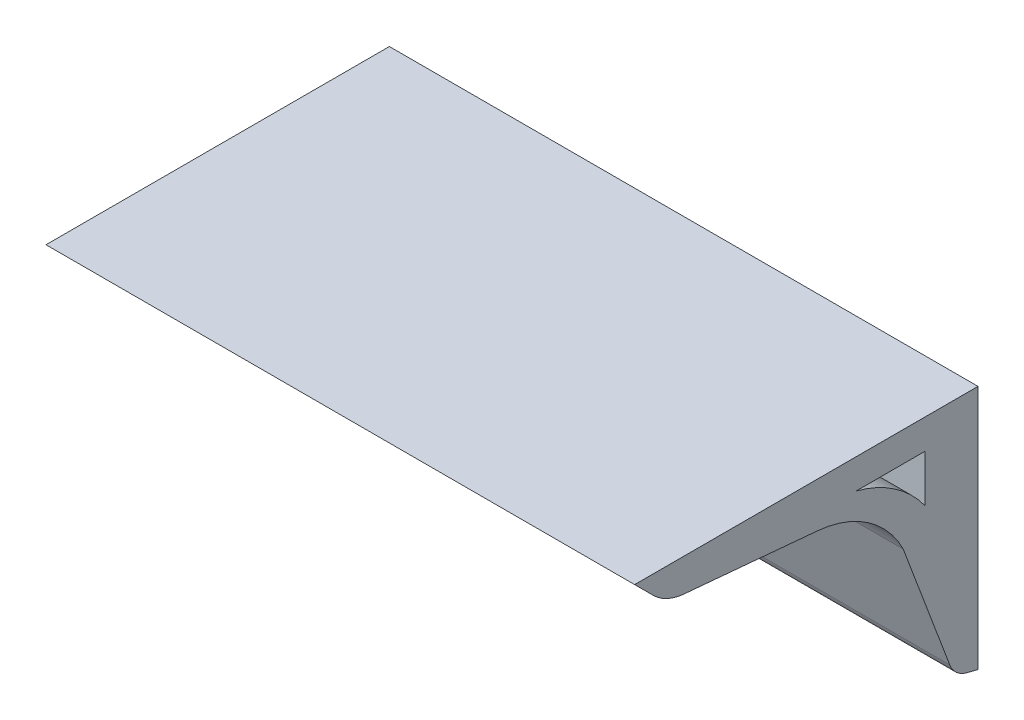
SolidWorks part; units mm, degrees
ref_plane "Alzado" through (0, 0, 0) normal (0, 0, 1) x (1, 0, 0)
ref_plane "Planta" through (0, 0, 0) normal (0, 1, 0) x (1, 0, 0)
ref_plane "Vista lateral" through (0, 0, 0) normal (1, 0, 0) x (0, 0, -1)
sketch "Croquis1" plane through (0, 0, 0) normal (0, 0, 1) x (1, 0, 0)
  line L1 (140.7009, 68.628) -> (260.7009, 68.628)
  line L2 (140.7009, 68.628) -> (140.7009, 18.628)
  line L3 (140.7009, 18.628) -> (260.7009, 18.628)
  line L4 (260.7009, 68.628) -> (260.7009, 18.628)
  dimension "D1" = 50
  dimension "D2" = 120
extrude "Saliente-Extruir1" add sketch "Croquis1" along normal blind 70
sketch "Croquis2" plane through (260.7009, 0, 0) normal (1, 0, 0) x (0, 0, -1)
  line L0 (-70, 68.628) -> (-66.2039, 64.8319)
  line L1 (-60.0305, 61.9434) -> (-32.7141, 59.4815)
  line L3 (-15.2552, 47.5412) -> (-5.7407, 22.2913)
  line L4 (-2.2885, 19.2071) -> (0, 18.628)
  line L5 (0, 18.628) -> (-70, 18.628)
  line L6 (-70, 18.628) -> (-70, 68.628)
  line L8 (-10.777, 52.9202) -> (-10.777, 62.5711)
  line L9 (-10.777, 62.5711) -> (-24.8487, 62.5711)
  arc A0 (-32.7141, 59.4815) -> (-15.2552, 47.5412) centre (-34.6588, 37.9038) cw
  arc A1 (-66.2039, 64.8319) -> (-60.0305, 61.9434) centre (-59.1329, 71.903) ccw
  arc A2 (-5.7407, 22.2913) -> (-2.2885, 19.2071) centre (-1.0619, 24.0543) ccw
  arc A3 (-10.777, 52.9202) -> (-24.8487, 62.5711) centre (-31.0267, 38.479) ccw
  dimension "D1" = 10
  dimension "D2" = 5
extrude "Cortar-Extruir1" cut sketch "Croquis2" against normal blind 121
